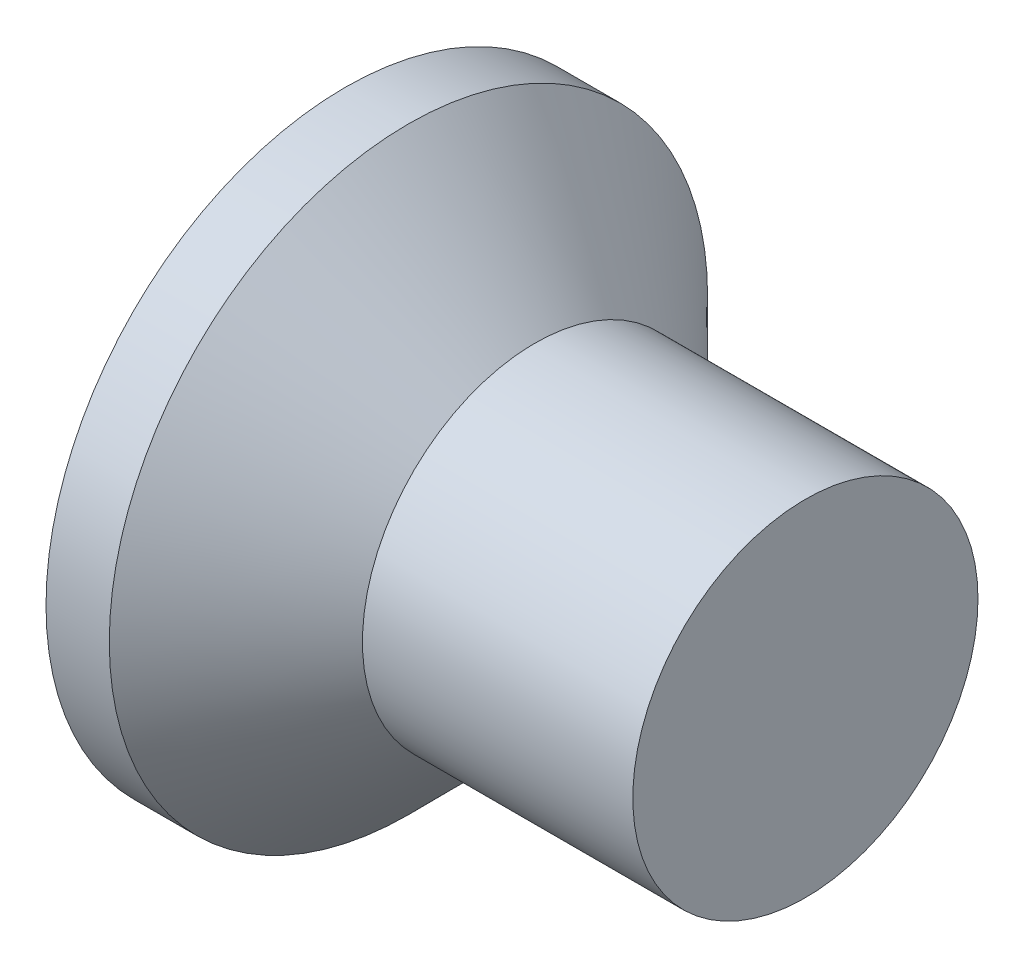
SolidWorks part; units mm, degrees
ref_plane "Front" through (0, 0, 0) normal (0, 0, 1) x (1, 0, 0)
ref_plane "Top" through (0, 0, 0) normal (0, 1, 0) x (1, 0, 0)
ref_plane "Right" through (0, 0, 0) normal (1, 0, 0) x (0, 0, -1)
sketch "Sketch1" plane through (0, 0, 0) normal (0, 0, 1) x (1, 0, 0)
  line L0 (4, 1.5) -> (2.65, 1.5)
  line L1 (2.65, 1.5) -> (1.65, 1.5)
  line L2 (1.65, 1.5) -> (0.55, 2.6)
  line L3 (0.55, 2.6) -> (0, 2.6)
  line L4 (4, 1.5) -> (4, 0)
  line L5 (4.5158, 0) -> (-89.8219, 0) construction
  line L6 (4, 0) -> (0, 0)
  line L7 (0, 2.6) -> (0, 0)
  dimension "D1" = 45
  dimension "d" = 3
  dimension "dk" = 5.2
  dimension "l" = 4
  dimension "k" = 1.65
  dimension "a" = 1
revolve "Base" add sketch "Sketch1" angle 360 about L5
cosmetic thread "ThreadCosmetic1" [suppressed] parameters "bb"=2.35, "THD_MINOR"=2.459
sketch "Sketch6" plane through (0, 0, 0) normal (1, 0, 0) x (0, 0, -1)
  line L0 (-1.9271, 0) -> (2.0512, 0) construction
  line L1 (0, 1.8651) -> (0, -2.0207) construction
  line L2 (0.32, 0.32) -> (0.32, 1.6)
  line L3 (0.32, 1.6) -> (-0.32, 1.6)
  line L4 (-0.32, 0.32) -> (-0.32, 1.6)
  line L5 (0.32, 0.32) -> (1.6, 0.32)
  line L6 (1.6, 0.32) -> (1.6, -0.32)
  line L7 (-1.6, 0.32) -> (-1.6, -0.32)
  line L8 (-0.32, 0.32) -> (-1.6, 0.32)
  line L9 (-0.32, -0.32) -> (-1.6, -0.32)
  line L10 (0.32, -0.32) -> (1.6, -0.32)
  line L11 (-0.32, -0.32) -> (-0.32, -1.6)
  line L12 (0.32, -1.6) -> (-0.32, -1.6)
  line L13 (0.32, -0.32) -> (0.32, -1.6)
  point P16 (-1.6, 0)
  point P17 (1.6, 0)
  dimension "D1" = 0.64
  dimension "m" = 3.2
extrude "CrossRecess" cut sketch "Sketch6" along normal blind 0.825
draft "Draft9" type of draft neutral plane draft angle 30 faces to draft 4 face at (0.4125, 1.6, 0) face at (0.4125, 0, 1.6) face at (0.4125, -1.6, 0) face at (0.4125, 0, -1.6) neutral plane through (0, 2.6, 0) neutral plane normal (-1, 0, 0) parameters "D1"=30
fillet "Fillet5" radius 0.3 4 edges at (0.4125, -0.32, -0.32) (0.4125, 0.32, -0.32) (0.4125, 0.32, 0.32) (0.4125, -0.32, 0.32)
sketch "Sketch7" plane through (0, 0, 0) normal (1, 0, 0) x (0, 0, -1)
  line L0 (-2.0126, 0) -> (1.9757, 0) construction
  line L1 (0, 1.9314) -> (0, -2.0126) construction
  line L2 (0, 0) -> (1.5555, 1.5555) construction
  line L3 (0, 0.4782) -> (1.1314, 1.1314)
  line L4 (-1.5402, 1.5402) -> (0, 0) construction
  line L5 (0.4782, 0) -> (1.1314, 1.1314)
  line L6 (0, -0.4782) -> (1.1314, -1.1314)
  line L7 (0.4782, 0) -> (1.1314, -1.1314)
  line L8 (-0.4782, 0) -> (-1.1314, -1.1314)
  line L9 (0, -0.4782) -> (-1.1314, -1.1314)
  line L10 (-0.4782, 0) -> (-1.1314, 1.1314)
  line L11 (0, 0.4782) -> (-1.1314, 1.1314)
  dimension "D3" = 15
extrude "Cut-Extrude3" [suppressed] cut sketch "Sketch7" along normal blind 10 draft 20
sketch "Sketch8" plane through (0, 0, 0) normal (0, 0, 1) x (1, 0, 0)
  line L0 (-21, 1.7705) -> (-22.25, 1.5)
  line L1 (-22.25, 1.5) -> (1.65, 1.5)
  line L3 (4, -1.5) -> (4, 1.5) construction
  line L6 (1.65, 1.5) -> (1.65, 6.5)
  line L7 (1.65, 6.5) -> (-21, 6.5)
  line L8 (-21, 6.5) -> (-21, 1.7705)
  line L9 (62.4753, 0.2705) -> (52.9594, 0.2705) construction
  dimension "D1" = 5
  dimension "x" = 1.25
  dimension "b" = 25
sketch "Sketch9" plane through (0, 0, 0) normal (0, 0, 1) x (1, 0, 0)
  line L0 (4, 1.2657) -> (4.1353, 1.5)
  line L1 (4.1353, 1.5) -> (4.1353, 1.7705)
  line L2 (4.1353, 1.7705) -> (3.8647, 1.7705)
  line L3 (3.8647, 1.7705) -> (3.8647, 1.5)
  line L4 (3.8647, 1.5) -> (4, 1.2657)
  line L5 (0, 0) -> (73.843, 0) construction
  line L6 (4, -1.5) -> (4, 1.5) construction
  dimension "D1" = 3
  dimension "D2" = 0.2705
revolve "Cut-Revolve10" [suppressed] cut sketch "Sketch9" angle 360 about L5
pattern_linear "LPattern10" [suppressed] count 7 spacing 0.3246 along (1, 0, 0)
equation "\"D1@Sketch6\" = \"m@Sketch6\" / 5"
equation "\"D1@CrossRecess\" = \"k@Sketch1\" / 2"
equation "\"D1@Sketch9\" = \"d@Sketch1\""
equation "\"D2@Sketch9\" =  ( \"d@Sketch1\" - \"THD_MINOR@ThreadCosmetic1\" )  / 2"
equation "\"D3@LPattern10\" = \"D2@Sketch9\" * 1.2"
equation "\"D1@LPattern10\" = \"bb@ThreadCosmetic1\" / \"D3@LPattern10\" "
